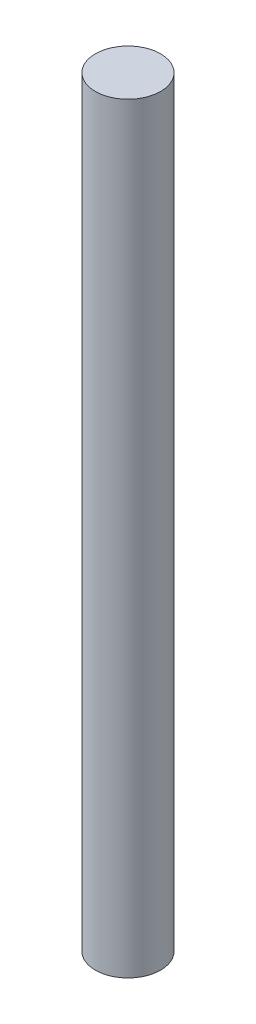
SolidWorks part; units mm, degrees
ref_plane "前视基准面" through (0, 0, 0) normal (0, 0, 1) x (1, 0, 0)
ref_plane "上视基准面" through (0, 0, 0) normal (0, 1, 0) x (1, 0, 0)
ref_plane "右视基准面" through (0, 0, 0) normal (1, 0, 0) x (0, 0, -1)
other "Configuration Table"
sketch "草图1" plane through (0, 0, 0) normal (0, 1, 0) x (1, 0, 0)
  circle A0 centre (0, 0) radius 1.5
  dimension "D1" = 3
extrude "凸台-拉伸1" add sketch "草图1" along normal blind 35
